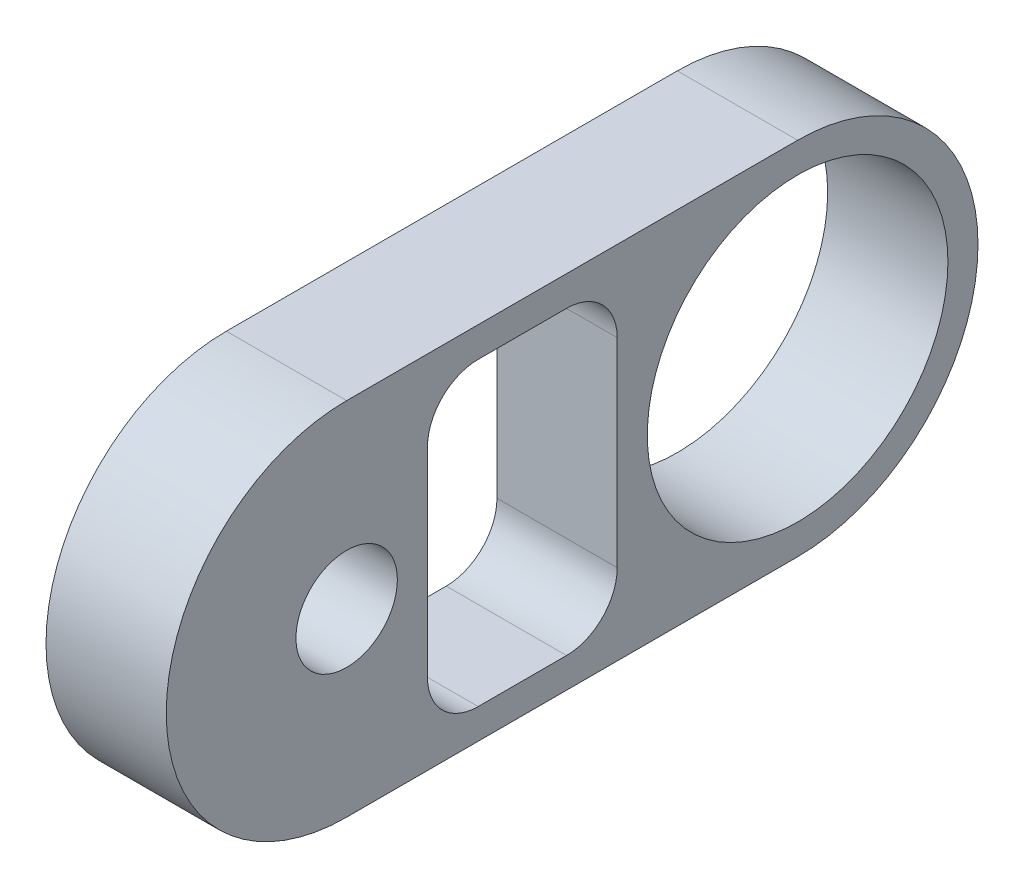
SolidWorks part; units mm, degrees
material "Ti-6Al-4VSolution treated and aged (SS)"
ref_plane "Front Plane" through (0, 0, 0) normal (1, 0, 0) x (0, 1, 0)
ref_plane "Top Plane" through (0, 0, 0) normal (0, 0, 1) x (0, 1, 0)
ref_plane "Right Plane" through (0, 0, 0) normal (0, 1, 0) x (-1, 0, 0)
sketch "Sketch1" plane through (0, 0, 0) normal (1, 0, 0) x (0, 1, 0)
  line L0 (-60.8736, 15.3619) -> (-60.8736, -22.7381)
  line L1 (-30.3936, -22.7381) -> (-30.3936, 15.3619)
  arc A0 (-60.8736, 15.3619) -> (-30.3936, 15.3619) centre (-45.6336, 15.3619) cw
  arc A1 (-60.8736, -22.7381) -> (-30.3936, -22.7381) centre (-45.6336, -22.7381) ccw
  circle A2 centre (-45.6336, -22.7381) radius 12.7
  circle A3 centre (-45.6336, 15.3619) radius 4.285
  dimension "D1" = 25.4
  dimension "D2" = 8.57
  dimension "D3" = 30.48
  dimension "D4" = 38.1
extrude "Boss-Extrude1" add sketch "Sketch1" along normal blind 10.16
sketch "Sketch2" plane through (10.16, 0, 0) normal (1, 0, 0) x (0, 1, 0)
  line L0 (-60.8736, 15.3619) -> (-60.8736, -22.7381) construction
  line L1 (-58.3336, 8.5369) -> (-32.9336, 8.5369)
  line L2 (-58.3336, 8.5369) -> (-58.3336, -7.4981)
  line L3 (-58.3336, -7.4981) -> (-32.9336, -7.4981)
  line L4 (-32.9336, 8.5369) -> (-32.9336, -7.4981)
  line L5 (-30.3936, -22.7381) -> (-30.3936, 15.3619) construction
  circle A0 centre (-45.6336, -22.7381) radius 12.7 construction
  circle A1 centre (-45.6336, 15.3619) radius 4.285 construction
  dimension "D1" = 15.24
  dimension "D2" = 2.54
  dimension "D3" = 6.825
  dimension "D4" = 2.54
extrude "Cut-Extrude1" cut sketch "Sketch2" against normal through all
fillet "Fillet1" radius 4.285 4 edges at (5.08, -58.3336, 8.5369) (5.08, -58.3336, -7.4981) (5.08, -32.9336, -7.4981) (5.08, -32.9336, 8.5369)
equation "\"d_max\"= 1.000"
equation "\"F\"= 1200"
equation "\"YieldStr\"= 120000.0006"
equation "\"SF\"= 4"
equation "\"A_min\"= ( \"F\" * \"SF\" ) / ( \"YieldStr\" )"
equation "\"x\"= 0.10"
equation "\"y\"= \"A_min\" / \"x\""
equation "\"width\"= 2 * ( ( \"d_max\" / 2 ) + \"x\" )"
equation "\"d_top\"= 0.3374"
equation "\"D1@Sketch1\"=\"d_max\""
equation "\"D2@Sketch1\"=\"d_top\""
equation "\"D3@Sketch1\"=\"width\""
equation "\"r_max\"= \"d_max\" / 2"
equation "\"D4@Sketch1\"=\"d_max\"+\"r_max\""
equation "\"D1@Boss-Extrude1\"=\"y\""
equation "\"D1@Sketch2\"=\"r_max\"+\"x\""
equation "\"D2@Sketch2\"=\"x\""
equation "\"D3@Sketch2\"=\"d_top\"/2+\"x\""
equation "\"D1@Fillet1\"=\"d_top\"/2"
